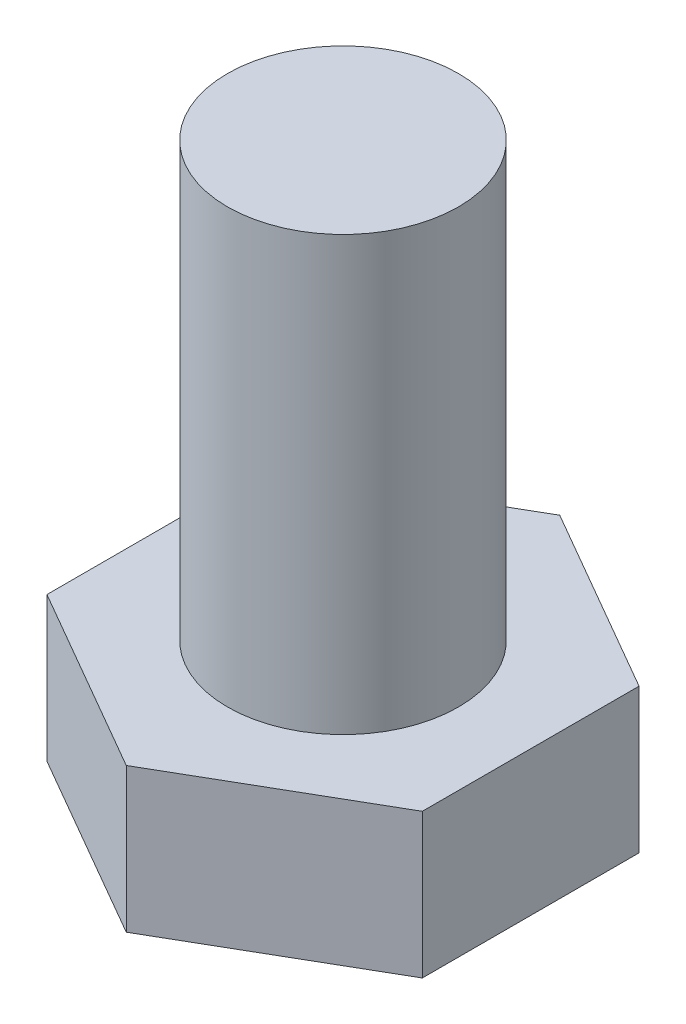
SolidWorks part; units mm, degrees
material "Galvanized Steel"
ref_plane "Front Plane" through (0, 0, 0) normal (0, 0, 1) x (1, 0, 0)
ref_plane "Top Plane" through (0, 0, 0) normal (0, 1, 0) x (1, 0, 0)
ref_plane "Right Plane" through (0, 0, 0) normal (1, 0, 0) x (0, 0, -1)
sketch "Sketch1" plane through (0, 0, 0) normal (0, 1, 0) x (1, 0, 0)
  line L1 (0, 7.5056) -> (-6.5, 3.7528)
  line L2 (-6.5, 3.7528) -> (-6.5, -3.7528)
  line L3 (-6.5, -3.7528) -> (0, -7.5056)
  line L4 (0, -7.5056) -> (6.5, -3.7528)
  line L5 (6.5, -3.7528) -> (6.5, 3.7528)
  line L6 (6.5, 3.7528) -> (0, 7.5056)
  circle A0 centre (0, 0) radius 6.5 construction
  dimension "D1" = 13
extrude "Boss-Extrude1" add sketch "Sketch1" along normal blind 5
sketch "Sketch2" plane through (0, 5, 0) normal (0, 1, 0) x (1, 0, 0)
  circle A0 centre (0, 0) radius 4
  dimension "D1" = 8
extrude "Boss-Extrude2" add sketch "Sketch2" along normal blind 15
